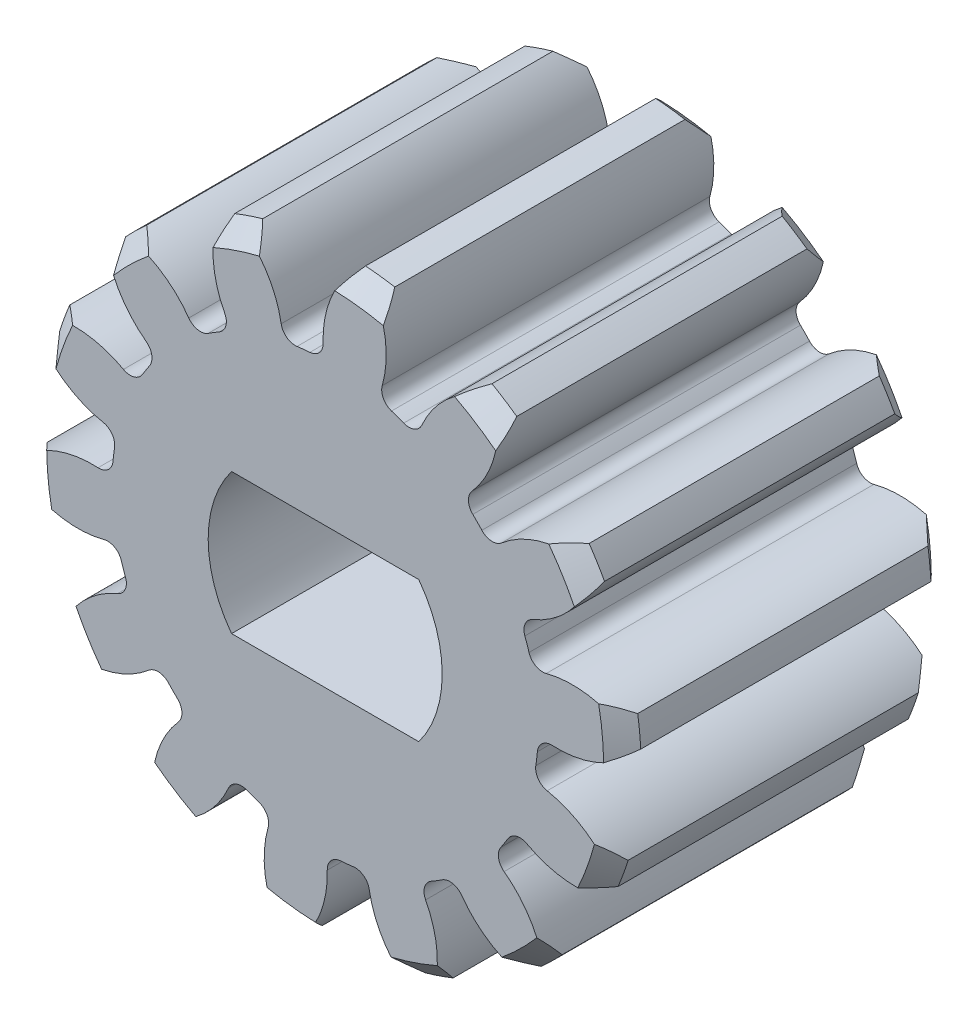
SolidWorks part; units mm, degrees
ref_plane "Front" through (0, 0, 0) normal (0, 0, 1) x (1, 0, 0)
ref_plane "Top" through (0, 0, 0) normal (0, 1, 0) x (1, 0, 0)
ref_plane "Right" through (0, 0, 0) normal (1, 0, 0) x (0, 0, -1)
sketch "Sketch3" plane through (0, 0, 0) normal (0, 0, 1) x (1, 0, 0)
  circle A0 centre (0, 0) radius 6.35
  dimension "od" = 12.7
extrude "gearBody" add sketch "Sketch3" along normal blind 7
chamfer "Chamfer1" distance 0.4 angle 45 2 edges at (6.35, 0, 7) (6.35, 0, 0)
sketch "Sketch2" plane through (0, 0, 0) normal (0, 0, 1) x (1, 0, 0)
  line L0 (0, 0) -> (4.9698, 2.0586) construction
  line L1 (6.3909, -2.4377) -> (0, 0) construction
  line L2 (0, 0) -> (36.3143, 0) construction
  line L3 (5.5558, -0.0668) -> (5.4064, -1.2815) construction
  line L5 (5.4811, -0.6742) -> (0, 0) construction
  line L7 (0, 0) -> (5.3793, 0) construction
  arc A0 (5.3782, -0.108) -> (5.244, -1.1986) centre (0, 0) ccw construction
  arc A1 (6.3413, 0.3324) -> (6.0717, -1.8592) centre (0, 0) ccw construction
  arc A2 (5.5558, -0.0668) -> (5.4064, -1.2815) centre (0, 0) ccw construction
  arc A3 (4.4999, -0.6928) -> (4.5337, -0.4183) centre (0, 0) ccw
  arc A4 (6.3909, -2.4377) -> (4.7423, -1.0371) centre (4.3228, -3.2015) ccw
  arc A5 (6.3909, -2.4377) -> (6.7912, 0.8163) centre (0, 0) ccw
  arc A6 (6.7912, 0.8163) -> (4.8523, -0.143) centre (4.9698, 2.0586) cw
  arc A7 (4.5337, -0.4183) -> (4.8523, -0.143) centre (4.8361, -0.4462) cw
  arc A8 (4.7423, -1.0371) -> (4.4999, -0.6928) centre (4.8001, -0.739) cw
  point P6 (6.7912, 0.8163)
  point P22 (6.3909, -2.4377)
  dimension "baseDia" = 10.7585
  dimension "od" = 12.7
  dimension "pd" = 11.1125
  dimension "rd" = 9.1059
  dimension "rFillet" = 0.3037
  dimension "pointX" = 6.7912
  dimension "pointY" = 0.8163
  dimension "CTT" = 1.2148
  dimension "flankCenterAngle" = 22.5
extrude "toothCut" cut sketch "Sketch2" along normal through all
pattern_circular "CirPattern1" count 14 over 360 about axis through (0, 0, 0) along (0, 0, 1) of "toothCut"
sketch "hub1Dia" plane through (0, 0, 0) normal (0, 0, -1) x (-1, 0, 0)
  circle A0 centre (0, 0) radius 12.7
  dimension "hub1Dia" = 25.4
sketch "hub2Dia" plane through (0, 0, 7) normal (0, 0, 1) x (1, 0, 0)
  circle A0 centre (0, 0) radius 12.7
  dimension "hub2dia" = 25.4
sketch "Sketch4" plane through (0, 0, 0) normal (0, 0, -1) x (-1, 0, 0)
  line L0 (-2, 1.5) -> (2, 1.5)
  line L1 (-2, -1.5) -> (2, -1.5)
  arc A0 (-2, 1.5) -> (-2, -1.5) centre (0, 0) ccw
  arc A1 (2, -1.5) -> (2, 1.5) centre (0, 0) ccw
  dimension "D1" = 5
  dimension "D2" = 1.5
  dimension "D3" = 1.5
extrude "Cut-Extrude1" cut sketch "Sketch4" against normal blind 10
